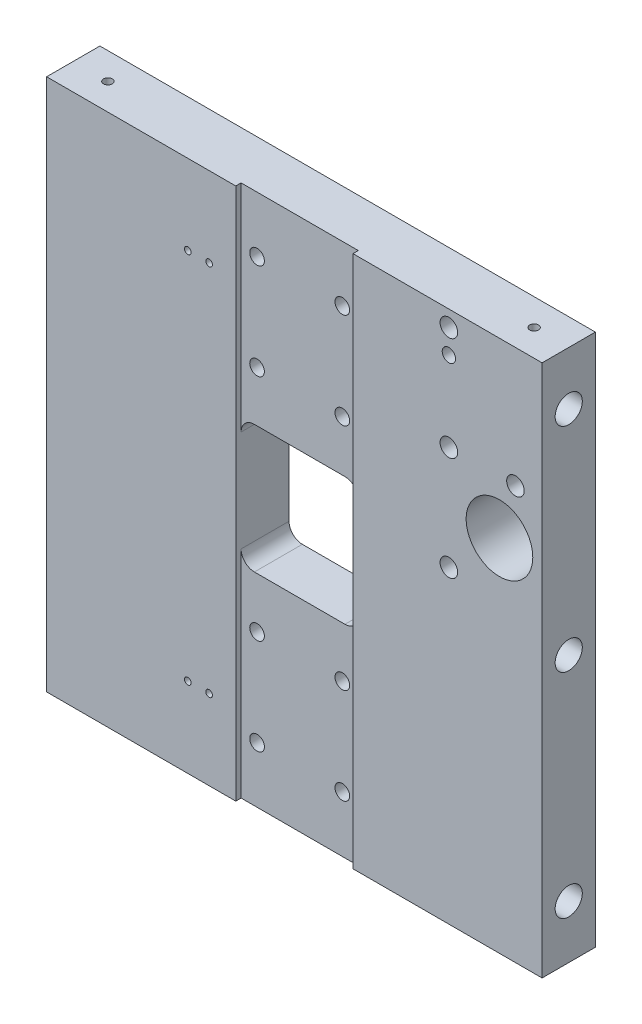
SolidWorks part; units mm, degrees
material "6061"
ref_plane "前视" through (0, 0, 0) normal (0, 0, 1) x (1, 0, 0)
ref_plane "上视" through (0, 0, 0) normal (0, 1, 0) x (1, 0, 0)
ref_plane "右视" through (0, 0, 0) normal (1, 0, 0) x (0, 0, -1)
sketch "草图1" plane through (0, 0, 0) normal (0, 0, 1) x (1, 0, 0)
  line L1 (-93, -100) -> (93, -100)
  line L2 (-93, -100) -> (-93, 100)
  line L3 (-93, 100) -> (93, 100)
  line L4 (93, -100) -> (93, 100)
  line L5 (-93, -100) -> (93, 100) construction
  line L6 (-93, 100) -> (93, -100) construction
  point P0 (0, 0)
  dimension "D1" = 186
  dimension "D2" = 200
extrude "凸台-拉伸1" add sketch "草图1" along normal blind 20
hole_wizard "M12 螺纹孔1" positions "草图3" profile "草图2" tap size "M12" standard "Gb"
sketch "草图3" plane through (-93, 0, 0) normal (-1, 0, 0) x (0, 0, 1)
  line L0 (10, 100) -> (10, 80) construction
  line L1 (20, 100) -> (0, 100) construction
  point P0 (10, 80)
  point P9 (10, 0)
  point P11 (10, -80)
  dimension "D1" = 20
  dimension "D2" = 80
  dimension "D3" = 160
sketch "草图2" plane through (-93, 80, 10) normal (0, 1, 0) x (0, 0, 1)
  line L0 (0, 0) -> (0, 30.0644)
  line L1 (0, 30.0644) -> (5.1, 27)
  line L2 (5.1, 27) -> (5.1, 0)
  line L5 (5.1, 0) -> (0, 0)
  line L10 (0, 30.0644) -> (-5.1, 27) construction
  line L11 (0, -6.35) -> (0, 107.95) construction
  dimension "螺纹孔钻头直径" = 10.2
  dimension "螺纹孔钻头深度" = 27
  dimension "导头角度" = 118
cosmetic thread "孔螺蚊线1" parameters "D1"=24, "D2"=12
cosmetic thread "孔螺蚊线2" parameters "D1"=24, "D2"=12
cosmetic thread "孔螺蚊线3" parameters "D1"=24, "D2"=12
mirror "镜向1" about plane through (0, 0, 0) normal (1, 0, 0) of "M12 螺纹孔1"
sketch "草图4" plane through (0, 0, 20) normal (0, 0, 1) x (1, 0, 0)
  line L0 (93, 100) -> (-93, 100) construction
  line L1 (-22, 100) -> (22, 100)
  line L2 (-22, 100) -> (-22, -100)
  line L3 (-22, -100) -> (22, -100)
  line L4 (22, 100) -> (22, -100)
  line L5 (-22, 100) -> (22, -100) construction
  line L6 (-22, -100) -> (22, 100) construction
  line L7 (-93, -100) -> (93, -100) construction
  line L9 (0, 100) -> (0, 0) construction
  point P0 (0, 0)
  dimension "D1" = 44
extrude "切除-拉伸1" cut sketch "草图4" against normal blind 2
hole_wizard "打孔尺寸根据内六角圆柱头螺钉的类型2" positions "草图6" profile "草图5" counterbore size "M5" standard "Gb" end condition through all
sketch "草图6" plane through (0, 0, 0) normal (0, 0, -1) x (-1, 0, 0)
  line L0 (0, 100) -> (0, 0) construction
  line L1 (0, 0) -> (22, 0) construction
  line L2 (22, 100) -> (22, -100) construction
  line L3 (-22, 100) -> (22, 100) construction
  line L4 (-93, 100) -> (93, 100) construction
  point P0 (16, 79)
  point P2 (16, 43)
  point P19 (-16, 43)
  point P20 (-16, 79)
  point P21 (-16, -79)
  point P22 (-16, -43)
  point P23 (16, -43)
  point P24 (16, -79)
  dimension "D1" = 32
  dimension "D2" = 36
  dimension "D3" = 21
sketch "草图5" plane through (-16, 79, 0) normal (1, 0, 0) x (0, 1, 0)
  line L0 (0, 0) -> (0, 20)
  line L1 (0, 20) -> (2.75, 20)
  line L3 (2.75, 20) -> (2.75, 6.5)
  line L4 (2.75, 6.5) -> (5, 6.5)
  line L5 (5, 6.5) -> (5, 0)
  line L7 (5, 0) -> (0, 0)
  line L11 (0, -6.35) -> (0, 107.95) construction
  dimension "通孔孔直径" = 5.5
  dimension "通孔孔深度" = 20
  dimension "柱形沉头孔直径" = 10
  dimension "柱形沉头孔深度" = 6.5
hole_wizard "打孔尺寸根据内六角圆柱头螺钉的类型2" positions "草图8" profile "草图7" counterbore size "M6" standard "Gb" end condition through all
sketch "草图8" plane through (0, 0, 0) normal (0, 0, -1) x (-1, 0, 0)
  line L0 (-100, 55) -> (-19.7851, 55) construction
  line L2 (-93, 100) -> (93, 100) construction
  point P0 (-58, 94)
  point P9 (-58, 55)
  point P13 (-58, 16)
  point P19 (0, 100)
  point P21 (-83, 55)
  dimension "D1" = 78
  dimension "D2" = 58
  dimension "D3" = 45
  dimension "D4" = 25
sketch "草图7" plane through (58, 94, 0) normal (1, 0, 0) x (0, 1, 0)
  line L0 (0, 0) -> (0, 20)
  line L1 (0, 20) -> (3.3, 20)
  line L3 (3.3, 20) -> (3.3, 6.8)
  line L4 (3.3, 6.8) -> (5.5, 6.8)
  line L5 (5.5, 6.8) -> (5.5, 0)
  line L7 (5.5, 0) -> (0, 0)
  line L11 (0, -6.35) -> (0, 107.95) construction
  dimension "通孔孔直径" = 6.6
  dimension "通孔孔深度" = 20
  dimension "柱形沉头孔直径" = 11
  dimension "柱形沉头孔深度" = 6.8
hole_wizard "M4 螺纹孔1" positions "草图10" profile "草图9" tap size "M4" standard "Gb"
sketch "草图10" plane through (0, 100, 0) normal (0, 1, 0) x (1, 0, 0)
  line L0 (-93, -10) -> (0, -10) construction
  line L1 (-93, -20) -> (-93, 0) construction
  line L2 (0, -10) -> (0, 0) construction
  point P0 (-80, -10)
  point P13 (80, -10)
  dimension "D1" = 160
sketch "草图9" plane through (-80, 100, 10) normal (1, 0, 0) x (0, 0, 1)
  line L0 (0, 0) -> (0, 11.0914)
  line L1 (0, 11.0914) -> (1.65, 10.1)
  line L2 (1.65, 10.1) -> (1.65, 0)
  line L5 (1.65, 0) -> (0, 0)
  line L10 (0, 11.0914) -> (-1.65, 10.1) construction
  line L11 (0, -6.35) -> (0, 107.95) construction
  dimension "螺纹孔钻头直径" = 3.3
  dimension "螺纹孔钻头深度" = 10.1
  dimension "导头角度" = 118
cosmetic thread "孔螺蚊线4" parameters "D1"=7.8, "D2"=4
cosmetic thread "孔螺蚊线5" parameters "D1"=8, "D2"=4
sketch "草图11" plane through (0, 0, 0) normal (0, 0, -1) x (-1, 0, 0)
  line L0 (-16, 43) -> (16, -43) construction
  line L1 (-22, -100) -> (-22, 100) construction
  line L2 (-17, -24) -> (17, -24)
  line L3 (-22, -19) -> (-22, 19)
  line L4 (-17, 24) -> (17, 24)
  line L5 (22, -19) -> (22, 19)
  line L6 (-22, -24) -> (22, 24) construction
  line L7 (-22, 24) -> (22, -24) construction
  arc A0 (-17, -24) -> (-22, -19) centre (-17, -19) cw
  arc A1 (17, -24) -> (22, -19) centre (17, -19) ccw
  arc A2 (17, 24) -> (22, 19) centre (17, 19) cw
  arc A3 (-22, 19) -> (-17, 24) centre (-17, 19) cw
  circle A4 centre (16, 43) radius 5 construction
  point P4 (0, 0)
  dimension "D1" = 5
  dimension "D2" = 19
extrude "切除-拉伸2" cut sketch "草图11" against normal through all
hole_wizard "M4 螺纹孔2" positions "草图13" profile "草图12" tap size "M4" standard "Gb"
sketch "草图13" plane through (0, 0, 0) normal (0, 0, -1) x (-1, 0, 0)
  line L0 (-16, 79) -> (16, 79) construction
  line L1 (0, 79) -> (0, 62.474) construction
  line L2 (-93, 100) -> (93, 100) construction
  point P0 (-12.5, 65)
  point P11 (12.5, 65)
  dimension "D1" = 25
  dimension "D2" = 35
sketch "草图12" plane through (12.5, 65, 0) normal (1, 0, 0) x (0, 1, 0)
  line L0 (0, 0) -> (0, 11.0914)
  line L1 (0, 11.0914) -> (1.65, 10.1)
  line L2 (1.65, 10.1) -> (1.65, 0)
  line L5 (1.65, 0) -> (0, 0)
  line L10 (0, 11.0914) -> (-1.65, 10.1) construction
  line L11 (0, -6.35) -> (0, 107.95) construction
  dimension "螺纹孔钻头直径" = 3.3
  dimension "螺纹孔钻头深度" = 10.1
  dimension "导头角度" = 118
cosmetic thread "孔螺蚊线6" parameters "D1"=8, "D2"=4
cosmetic thread "孔螺蚊线7" parameters "D1"=8, "D2"=4
hole_wizard "M3 螺纹孔1" positions "草图15" profile "草图14" tap size "M3" standard "Gb"
sketch "草图15" plane through (0, 0, 20) normal (0, 0, 1) x (1, 0, 0)
  line L0 (-36, 100) -> (-36, 35.5688) construction
  line L1 (-22, 100) -> (-93, 100) construction
  line L2 (-22, 100) -> (-22, 19) construction
  line L3 (-93, -100) -> (-22, -100) construction
  point P0 (-32, 70)
  point P2 (-32, -70)
  point P10 (-40, -70)
  point P11 (-40, 70)
  dimension "D1" = 8
  dimension "D2" = 10
  dimension "D3" = 30
  dimension "D4" = 30
sketch "草图14" plane through (-32, 70, 20) normal (1, 0, 0) x (0, -1, 0)
  line L0 (0, 0) -> (0, 8.2511)
  line L1 (0, 8.2511) -> (1.25, 7.5)
  line L2 (1.25, 7.5) -> (1.25, 0)
  line L5 (1.25, 0) -> (0, 0)
  line L10 (0, 8.2511) -> (-1.25, 7.5) construction
  line L11 (0, -6.35) -> (0, 107.95) construction
  dimension "螺纹孔钻头直径" = 2.5
  dimension "螺纹孔钻头深度" = 7.5
  dimension "导头角度" = 118
cosmetic thread "孔螺蚊线8" parameters "D1"=6, "D2"=3
cosmetic thread "孔螺蚊线9" parameters "D1"=6, "D2"=3
cosmetic thread "孔螺蚊线10" parameters "D1"=6, "D2"=3
cosmetic thread "孔螺蚊线11" parameters "D1"=6, "D2"=3
hole_wizard "孔1" positions "草图17" profile "草图16" legacy end condition through all
sketch "草图17" plane through (0, 0, 20) normal (0, 0, 1) x (1, 0, 0)
  line L0 (93, -100) -> (93, 100) construction
  circle A0 centre (58, 55) radius 3.3 construction
  point P0 (77, 35)
  dimension "D1" = 16
  dimension "D2" = 20
sketch "草图16" plane through (77, 35, 20) normal (1, 0, 0) x (0, -1, 0)
  line L0 (0, 0) -> (0, 20)
  line L1 (0, 20) -> (12.5, 20)
  line L2 (12.5, 20) -> (12.5, 0)
  line L3 (12.5, 0) -> (0, 0)
  line L4 (0, 110) -> (0, -10) construction
  dimension "直径" = 25
  dimension "深度" = 20
hole_wizard "M6 螺纹孔1" positions "草图19" profile "草图18" tap size "M6" standard "Gb" end condition through all
sketch "草图19" plane through (0, 0, 0) normal (0, 0, -1) x (-1, 0, 0)
  circle A0 centre (-58, 55) radius 5.5 construction
  point P0 (-58, 85)
  dimension "D1" = 30
cosmetic thread "孔螺蚊线12" parameters "D2"=6
sketch "草图18" plane through (58, 85, 0) normal (1, 0, 0) x (0, 1, 0)
  line L0 (0, 0) -> (0, 20)
  line L1 (0, 20) -> (2.5, 20)
  line L2 (2.5, 20) -> (2.5, 0)
  line L5 (2.5, 0) -> (0, 0)
  line L11 (0, -6.35) -> (0, 107.95) construction
  dimension "通孔螺纹孔钻头直径" = 5
  dimension "通孔螺纹孔钻头深度" = 20
